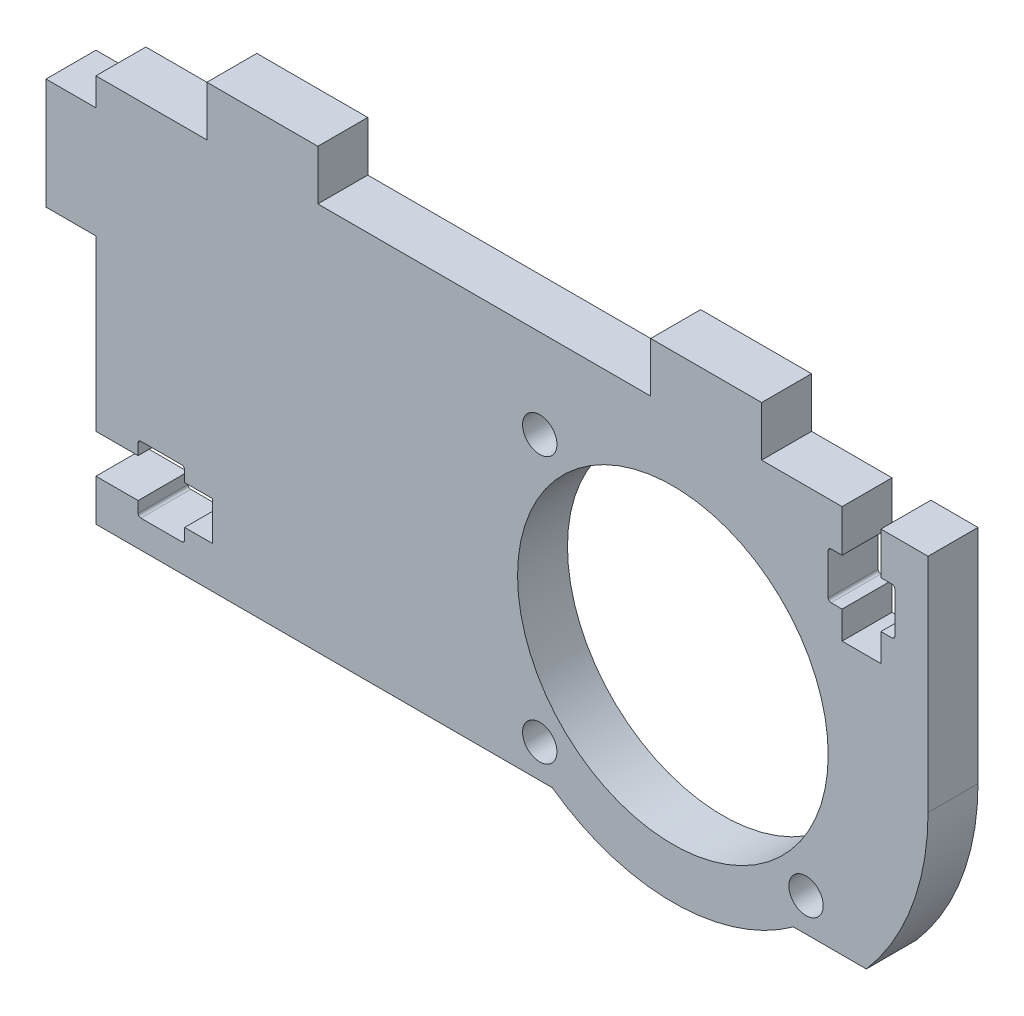
SolidWorks part; units mm, degrees
ref_plane "Front Plane" through (0, 0, 0) normal (0, 0, 1) x (1, 0, 0)
ref_plane "Top Plane" through (0, 0, 0) normal (0, 1, 0) x (1, 0, 0)
ref_plane "Right Plane" through (0, 0, 0) normal (1, 0, 0) x (0, 0, -1)
sketch "Sketch1" plane through (0, 0, 0) normal (0, 0, 1) x (1, 0, 0)
  line L0 (0, 0) -> (0, -35)
  line L1 (0, -35) -> (75, -35)
  line L2 (75, -35) -> (75, 0)
  line L3 (75, 0) -> (0, 0)
  dimension "D1" = 75
  dimension "D2" = 35
extrude "MainShape" add sketch "Sketch1" along normal blind 4.5
sketch "Sketch2" plane through (0, 0, 4.5) normal (0, 0, 1) x (1, 0, 0)
  line L0 (0, -2.5) -> (-4.5, -2.5)
  line L1 (0, 0) -> (0, -35) construction
  line L2 (-4.5, -2.5) -> (-4.5, -12.5)
  line L3 (-4.5, -12.5) -> (0, -12.5)
  line L4 (0, -12.5) -> (0, -2.5)
  line L5 (-4.5, -7.5) -> (0, -7.5) construction
  dimension "D1" = 10
  dimension "D2" = 4.5
  dimension "D3" = 7.5
extrude "RearTab" add sketch "Sketch2" against normal through all
sketch "Sketch3" plane through (0, 0, 4.5) normal (0, 0, 1) x (1, 0, 0)
  line L0 (75, 0) -> (0, 0) construction
  line L1 (10, 0) -> (20, 0)
  line L2 (10, 0) -> (10, 4.5)
  line L3 (10, 4.5) -> (20, 4.5)
  line L4 (20, 0) -> (20, 4.5)
  line L5 (15, 4.5) -> (15, 0) construction
  line L6 (50, 0) -> (60, 0)
  line L7 (50, 0) -> (50, 4.5)
  line L8 (50, 4.5) -> (60, 4.5)
  line L9 (60, 0) -> (60, 4.5)
  line L10 (55, 4.5) -> (55, 0) construction
  dimension "D1" = 4.5
  dimension "D2" = 10
  dimension "D3" = 40
  dimension "D4" = 15
extrude "Boss-Extrude3" add sketch "Sketch3" against normal through all
sketch "Sketch4" plane through (0, 0, 4.5) normal (0, 0, 1) x (1, 0, 0)
  line L0 (69, 0) -> (69, -10.5) construction
  line L1 (75, 0) -> (60, 0) construction
  line L2 (70.75, -10.5) -> (67.25, -10.5) construction
  line L3 (67.25, -10.5) -> (67.25, 0) construction
  line L4 (67.25, 0) -> (67.25, -3.8)
  line L5 (67.25, -3.8) -> (66.25, -3.8)
  line L6 (66, -4.05) -> (66, -7.75)
  line L7 (66.25, -8) -> (67.25, -8)
  line L8 (67.25, -8) -> (67.25, -10.5)
  line L9 (67.25, -10.5) -> (70.75, -10.5)
  line L10 (67.25, 0) -> (70.75, 0)
  line L11 (70.75, -10.5) -> (70.75, 0) construction
  line L12 (70.75, -8) -> (70.75, -10.5)
  line L13 (71.75, -8) -> (70.75, -8)
  line L14 (72, -4.05) -> (72, -7.75)
  line L15 (70.75, -3.8) -> (71.75, -3.8)
  line L16 (70.75, 0) -> (70.75, -3.8)
  arc A0 (66, -7.75) -> (66.25, -8) centre (66.25, -7.75) ccw
  arc A1 (66.25, -3.8) -> (66, -4.05) centre (66.25, -4.05) ccw
  arc A2 (71.75, -3.8) -> (72, -4.05) centre (71.75, -4.05) cw
  arc A3 (72, -7.75) -> (71.75, -8) centre (71.75, -7.75) cw
  point P13 (66, -8)
  point P16 (66, -3.8)
  point P27 (72, -3.8)
  point P28 (72, -8)
  dimension "D7" = 0.25
  dimension "D1" = 10.5
  dimension "D2" = 1.75
  dimension "D3" = 4.2
  dimension "D4" = 3
  dimension "D5" = 8
  dimension "D6" = 69
extrude "Cut-Extrude1" cut sketch "Sketch4" against normal through all
sketch "Sketch5" plane through (0, 0, 4.5) normal (0, 0, 1) x (1, 0, 0)
  line L0 (45.0208, 0) -> (45.0208, 4.5) construction
  line L1 (42.5416, 0) -> (47.5, 0)
  line L2 (42.5416, 0) -> (42.5416, -5.18)
  line L3 (42.5416, -5.18) -> (47.5, -5.18)
  line L4 (47.5, 0) -> (47.5, -5.18)
  line L5 (42.5416, 0) -> (47.5, -5.18) construction
  line L6 (42.5416, -5.18) -> (47.5, 0) construction
  line L7 (42, -4.18) -> (48, -4.18) construction
  line L8 (50, 0) -> (20, 0) construction
  line L9 (48, -4.18) -> (48, -1.18) construction
  line L10 (48, -2.68) -> (58, -2.68) construction
  line L11 (48, -4.18) -> (48, -1.18) construction
  line L12 (58, -1.18) -> (58, -4.18) construction
  line L13 (53, -2.68) -> (53, 0) construction
  line L14 (0, 0) -> (19.5, 0) construction
  line L15 (63.4584, -5.18) -> (58.5, 0) construction
  line L16 (63.4584, 0) -> (58.5, -5.18) construction
  line L17 (58.5, 0) -> (58.5, -5.18)
  line L18 (63.4584, -5.18) -> (58.5, -5.18)
  line L19 (63.4584, 0) -> (63.4584, -5.18)
  line L20 (63.4584, 0) -> (58.5, 0)
  line L21 (42.5416, -5.18) -> (47.5, 0) construction
  point P0 (45.0208, -2.59)
  point P27 (60.9792, -2.59)
  dimension "D1" = 1
  dimension "D2" = 0
  dimension "D3" = 0.5
extrude "Cut-Extrude2" [suppressed] cut sketch "Sketch5" against normal through all
sketch "Sketch6" plane through (0, 0, 4.5) normal (0, 0, 1) x (1, 0, 0)
  line L0 (52, -20) -> (40, -8) construction
  line L2 (52, -34) -> (52, -6) construction
  line L3 (52, -20) -> (38, -20) construction
  line L4 (52, -20) -> (64, -8) construction
  line L5 (52, -20) -> (64, -32) construction
  line L6 (52, -20) -> (40, -32) construction
  circle A0 centre (52, -20) radius 14
  circle A1 centre (40, -8) radius 1.55
  circle A3 centre (64, -32) radius 1.55
  circle A4 centre (40, -32) radius 1.55
  dimension "D1" = 28
  dimension "D4" = 3.1
  dimension "D2" = 52
  dimension "D3" = 20
  dimension "D5" = 12
  dimension "D6" = 45
extrude "Cut-Extrude3" cut sketch "Sketch6" against normal through all
sketch "Sketch7" plane through (0, 0, 4.5) normal (0, 0, 1) x (1, 0, 0)
  line L0 (0, -35) -> (62.8633, -35)
  arc A0 (41.1367, -35) -> (62.8633, -35) centre (52, -20) ccw
  circle A1 centre (52, -20) radius 14 construction
  circle A2 centre (64, -32) radius 1.55 construction
extrude "Boss-Extrude4" add sketch "Sketch7" against normal through all contours L0 A0
sketch "Sketch8" [suppressed] plane through (0, 0, 4.5) normal (0, 0, 1) x (1, 0, 0)
  line L1 (0, -35) -> (39.1367, -35) construction
  line L18 (15, -35) -> (15, -9.316) construction
  line L19 (6.3379, -28.8128) -> (15, -37.4749) construction
  line L20 (8.8128, -26.3379) -> (17.4749, -35) construction
  line L21 (6.3379, -28.8128) -> (8.8128, -26.3379) construction
  line L22 (15, -35) -> (7.5754, -27.5754) construction
  line L23 (15, -37.4749) -> (11.0756, -33.5504)
  line L24 (11.0756, -33.5504) -> (10.1917, -34.4343)
  line L25 (10.1917, -34.4343) -> (7.2218, -31.4645)
  line L26 (7.2218, -31.4645) -> (8.1057, -30.5806)
  line L27 (8.1057, -30.5806) -> (6.3379, -28.8128)
  line L28 (15, -37.4749) -> (15, -35)
  line L29 (17.4749, -35) -> (15, -35)
  line L30 (8.8128, -26.3379) -> (6.3379, -28.8128)
  line L31 (10.5806, -28.1057) -> (8.8128, -26.3379)
  line L32 (11.4645, -27.2218) -> (10.5806, -28.1057)
  line L33 (14.4343, -30.1917) -> (11.4645, -27.2218)
  line L34 (13.5504, -31.0756) -> (14.4343, -30.1917)
  line L35 (17.4749, -35) -> (13.5504, -31.0756)
  dimension "D7" = 15
extrude "Cut-Extrude4" [suppressed] cut sketch "Sketch8" against normal through all
sketch "Sketch10" [suppressed] plane through (0, 0, 4.5) normal (0, 0, 1) x (1, 0, 0)
  line L0 (17.4749, -35) -> (21.7175, -30.7574)
  line L1 (21.7175, -30.7574) -> (25.253, -34.2929)
  line L2 (25.253, -34.2929) -> (24.5459, -35)
  line L3 (17.4749, -35) -> (39.1367, -35) construction
  line L4 (24.5459, -35) -> (17.4749, -35)
  line L5 (17.4749, -35) -> (13.5504, -31.0756) construction
  dimension "D1" = 5
  dimension "D2" = 6
extrude "Cut-Extrude6" [suppressed] cut sketch "Sketch10" against normal through all
sketch "Sketch12" plane through (0, 0, 4.5) normal (0, 0, 1) x (1, 0, 0)
  line L0 (7.3224, -34.6526) -> (32.3224, -34.6526) construction
  circle A0 centre (32.3224, -34.6526) radius 5
  circle A1 centre (7.3224, -34.6526) radius 5
  dimension "D1" = 10
  dimension "D2" = 10
  dimension "D3" = 25
  dimension "D4" = 34.6526
  dimension "D5" = 7.3224
extrude "Boss-Extrude5" [suppressed] add sketch "Sketch12" against normal through all
sketch "Sketch11" plane through (0, 0, 4.5) normal (0, 0, 1) x (1, 0, 0)
  line L0 (0, -29.5) -> (10.5, -29.5) construction
  line L1 (0, -12.5) -> (0, -35) construction
  line L2 (10.5, -31.25) -> (10.5, -27.75) construction
  line L3 (10.5, -27.75) -> (0, -27.75) construction
  line L4 (0, -31.25) -> (0, -27.75)
  line L5 (0, -27.75) -> (3.8, -27.75)
  line L6 (3.8, -27.75) -> (3.8, -26.75)
  line L7 (4.05, -26.5) -> (7.75, -26.5)
  line L8 (8, -26.75) -> (8, -27.75)
  line L9 (8, -27.75) -> (10.5, -27.75)
  line L10 (10.5, -27.75) -> (10.5, -31.25)
  line L11 (10.5, -31.25) -> (0, -31.25) construction
  line L12 (8, -31.25) -> (10.5, -31.25)
  line L13 (8, -32.25) -> (8, -31.25)
  line L14 (4.05, -32.5) -> (7.75, -32.5)
  line L15 (3.8, -31.25) -> (3.8, -32.25)
  line L16 (0, -31.25) -> (3.8, -31.25)
  line L17 (-4.5, -2.5) -> (-4.5, -12.5) construction
  arc A0 (7.75, -26.5) -> (8, -26.75) centre (7.75, -26.75) cw
  arc A1 (3.8, -26.75) -> (4.05, -26.5) centre (4.05, -26.75) cw
  arc A2 (3.8, -32.25) -> (4.05, -32.5) centre (4.05, -32.25) ccw
  arc A3 (7.75, -32.5) -> (8, -32.25) centre (7.75, -32.25) ccw
  point P12 (8, -26.5)
  point P15 (3.8, -26.5)
  point P26 (3.8, -32.5)
  point P27 (8, -32.5)
  point P28 (-4.5, -7.5)
  dimension "D1" = 10.5
  dimension "D2" = 1.75
  dimension "D3" = 4.2
  dimension "D4" = 3
  dimension "D5" = 8
  dimension "D6" = 0.25
  dimension "D7" = 22
extrude "Cut-Extrude7" cut sketch "Sketch11" against normal through all
sketch "Sketch13" [suppressed] plane through (0, 0, 4.5) normal (0, 0, 1) x (1, 0, 0)
  circle A0 centre (7.3224, -34.6526) radius 1.55
  circle A1 centre (32.3224, -34.6526) radius 1.55
  arc A2 (2.3345, -35) -> (12.3103, -35) centre (7.3224, -34.6526) ccw construction
  arc A3 (27.3345, -35) -> (37.3103, -35) centre (32.3224, -34.6526) ccw construction
  dimension "D1" = 3.1
extrude "Cut-Extrude8" [suppressed] cut sketch "Sketch13" against normal through all
sketch "Sketch14" plane through (0, 0, 4.5) normal (0, 0, 1) x (1, 0, 0)
  line L0 (75, -35) -> (75, 0) construction
  line L1 (69.4356, -35) -> (75, -35)
  line L2 (75, -35) -> (75, -20)
  arc A0 (69.4356, -35) -> (75, -20) centre (52, -20) ccw
  circle A1 centre (52, -20) radius 14 construction
extrude "SmoothEdge" cut sketch "Sketch14" against normal through all
equation "\"X-ROD-SPACING\"=45"
equation "\"Y-ROD-SPACING\"=75"
equation "\"Z-ROD-SPACING\"=17.5"
equation "\"Y-BED-OFFSET\"=2"
equation "\"Y-BED-ROD-INSET\"=3.5"
equation "\"Y-BED-SCREW-SPACING\"=209"
equation "\"Y-BED-SCREW-CUTOUT-SLOT-HEIGHT\"=2"
equation "\"T-SLOT-NUT-FILLET-RADIUS\"=0.25"
equation "\"T-SLOT-SCREW-SHAFT-RADIUS\"=1.75"
equation "\"T-SLOT-SCREW-SHAFT-CUTOUT-LENGTH\"=10.5"
equation "\"T-SLOT-NUT-DEPTH\"=4.2"
equation "\"T-SLOT-NUT-WIDTH\"=3"
equation "\"T-SLOT-NUT-END-DISTANCE\"=8"
equation "\"ACRYLIC-THICKNESS\"=10"
equation "\"ACRYLIC-THICKNESS2\"=4.5"
equation "\"ACRYLIC-TAB-CUTOUT-SIZE\"=\"ACRYLIC-THICKNESS\"+\"ACRYLIC-TAB-TOLERANCE\"*2"
equation "\"ACRYLIC-TAB-TOLERANCE\"=.1"
equation "\"ACRYLIC-TAB-WIDTH\"=\"ACRYLIC-THICKNESS\""
equation "\"ACRYLIC-M3-HOLE\"=3.1"
equation "\"SMOOTHROD-CAP-SCREW-DISTANCE\"=20"
equation "\"FRAME-WIDTH-INNER\"=370"
equation "\"NEMA17-HOLE-SPACING\"=31"
equation "\"NEMA17-CENTRAL-CUTOUT\"=22.5"
equation "\"Z-BRACKET-REACH\"=55"
equation "\"Z-ROD-INSET\"=16"
equation "\"TOP-BRACKET-SPACING\"=40"
equation "\"SMOOTHROD-X-LENGTH\"=350"
equation "\"SMOOTHROD-Y-LENGTH\"=350"
equation "\"SMOOTHROD-Z-LENGTH\"=350"
equation "\"SMOOTHROD-TIGHTENING-HEADROOM\"=.25"
equation "\"LEADSCREW-Z-LENGTH\"=300"
equation "\"SCREW-LENGTH-FRAME\"=\"ACRYLIC-THICKNESS\" + 10"
equation "\"SCREW-LENGTH-MOTOR\"=\"ACRYLIC-THICKNESS\" + 5"
equation "\"SCREW-LENGTH-EXTRUDER\"=28"
equation "\"SCREW-HEAD-RADIUS\"=6"
equation "\"PRINTED-M3-HOLE\"=3.5"
equation "\"PRINTED-X-SMOOTHROD-DIAMETER\"=8.2"
equation "\"PRINTED-X-SMOOTHROD-CUTOUT\"=10"
equation "\"PRINTED-X-BASE-HEIGHT\"=10"
equation "\"PRINTED-LM8UU-CUTOUT-SIZE\"=15.25"
equation "\"PRINTED-LM8UU-CUTOUT-LENGTH\"=24.5"
equation "\"PRINTED-X-IDLER-HEIGHT\"=16"
equation "\"PRINTED-M3-NUT-AF\"=6.25"
equation "\"PSU-MOUNTING-WIDTH\"=95"
equation "\"PSU-MOUNTING-HEIGHT\"=177"
equation "\"Y-BELT-TO-ROD-DISTANCE\"=20"
equation "\"SPOOL-HOLDER-ROD-SPACING\"=150"
equation "\"ACRYLIC-X-CARRIAGE-WIDTH\"=55"
equation "\"ACRYLIC-X-CARRIAGE-HEIGHT\"=75"
equation "\"ACRYLIC-X-CARRIAGE-LM8UU-CUTOUT-WIDTH\"=24.25"
equation "\"ACRYLIC-X-CARRIAGE-LM8UU-CUTOUT-HEIGHT\"=11.5"
equation "\"ACRYLIC-X-CARRIAGE-SCREW-SPACING-X\"=15"
equation "\"ACRYLIC-X-CARRIAGE-SCREW-SPACING-Y\"=33"
equation "\"ACRYLIC-X-CARRIAGE-CENTER-TAB-SPACING\"=14"
equation "\"ACRYLIC-X-CARRIAGE-EXTRUDER-OFFSET\"=26"
equation "\"ACRYLIC-X-CARRIAGE-EXTRUDER-ANGLE\"=90"
equation "\"ACRYLIC-X-CARRIAGE-EXTRUDER-SHELF-DEPTH\"=\"ACRYLIC-X-CARRIAGE-EXTRUDER-OFFSET\" + 28"
equation "\"ACRYLIC-X-CARRIAGE-EXTRUDER-BRACE-SPACING\"=23"
equation "\"ACRYLIC-X-CARRIAGE-EXTRUDER-BRACE-TAB-OFFSET\"=20"
equation "\"ACRYLIC-X-CARRIAGE-EXTRUDER-BRACE-HEIGHT\"=35"
equation "\"ACRYLIC-X-CARRIAGE-EXTRUDER-BRACE-SCREW-SPACING\"=22"
equation "\"ACRYLIC-X-CARRIAGE-DUAL-WIDTH-MULTIPLIER\"=1.65"
equation "\"ACRYLIC-X-CARRIAGE-DUAL-HOTEND-SPACING\"=42"
equation "\"ACRYLIC-X-CARRIAGE-DUAL-WIDTH\"=75"
equation "\"ACRYLIC-X-CARRIAGE-DUAL-FAN-OFFSET\"=52"
equation "\"ACRYLIC-X-CARRIAGE-DUAL-FAN-HEIGHT\"=20"
equation "\"ACRYLIC-X-CARRIAGE-DUAL-HOTEND-SEPARATION\"=36"
equation "\"ACRYLIC-X-CARRIAGE-DUAL-MOUNT-PLATE-DEPTH\"=75"
equation "\"ACRYLIC-X-CARRIAGE-DUAL-MOUNT-BRACE-WIDTH\"=33"
equation "\"ACRYLIC-X-CARRIAGE-DUAL-MOUNT-SCREW-WIDTH\"=40"
equation "\"BLOWER-FAN-WIDTH\"=15"
equation "\"D1@Sketch1\"=\"ACRYLIC-X-CARRIAGE-DUAL-MOUNT-PLATE-DEPTH\""
equation "\"D2@Sketch1\"=\"ACRYLIC-X-CARRIAGE-EXTRUDER-BRACE-HEIGHT\""
equation "\"D1@MainShape\" = \"ACRYLIC-THICKNESS2\""
equation "\"D1@Sketch2\"=\"ACRYLIC-TAB-WIDTH\""
equation "\"D2@Sketch2\"=\"ACRYLIC-THICKNESS2\""
equation "\"D1@Sketch3\"=\"ACRYLIC-THICKNESS2\""
equation "\"D2@Sketch3\"=\"ACRYLIC-TAB-WIDTH\""
equation "\"D1@Sketch4\"=\"T-SLOT-SCREW-SHAFT-CUTOUT-LENGTH\""
equation "\"D2@Sketch4\"=\"T-SLOT-SCREW-SHAFT-RADIUS\""
equation "\"D3@Sketch4\"=\"T-SLOT-NUT-DEPTH\""
equation "\"D4@Sketch4\"=\"T-SLOT-NUT-WIDTH\""
equation "\"D5@Sketch4\"=\"T-SLOT-NUT-END-DISTANCE\""
equation "\"D7@Sketch4\"=\"T-SLOT-NUT-FILLET-RADIUS\""
equation "\"D2@Sketch6\"=\"ACRYLIC-X-CARRIAGE-DUAL-FAN-OFFSET\""
equation "\"D3@Sketch6\"=\"ACRYLIC-X-CARRIAGE-DUAL-FAN-HEIGHT\""
equation "\"D4@Sketch6\"=\"ACRYLIC-M3-HOLE\""
equation "\"D1@Sketch11\"=\"T-SLOT-SCREW-SHAFT-CUTOUT-LENGTH\""
equation "\"D2@Sketch11\"=\"T-SLOT-SCREW-SHAFT-RADIUS\""
equation "\"D3@Sketch11\"=\"T-SLOT-NUT-DEPTH\""
equation "\"D4@Sketch11\"=\"T-SLOT-NUT-WIDTH\""
equation "\"D5@Sketch11\"=\"T-SLOT-NUT-END-DISTANCE\""
equation "\"D6@Sketch11\"=\"T-SLOT-NUT-FILLET-RADIUS\""
equation "\"D1@Sketch13\"=\"ACRYLIC-M3-HOLE\""
